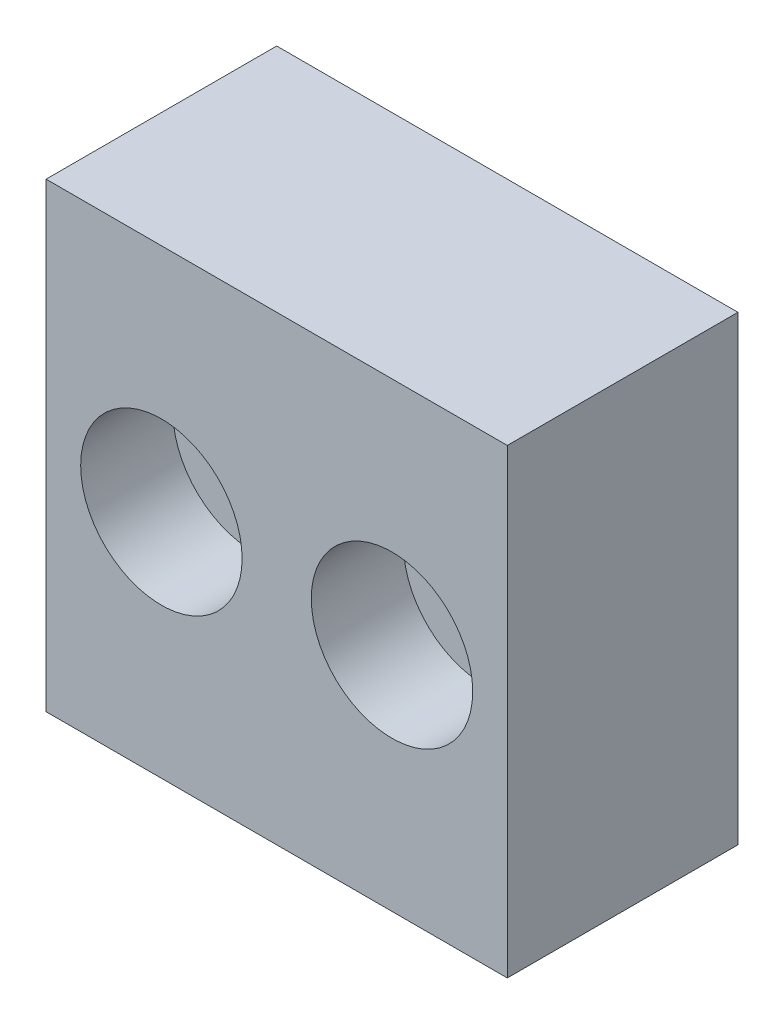
SolidWorks part; units mm, degrees
material "ASTM A36 Aço"
ref_plane "Plano frontal" through (0, 0, 0) normal (0, 0, 1) x (1, 0, 0)
ref_plane "Plano superior" through (0, 0, 0) normal (0, 1, 0) x (1, 0, 0)
ref_plane "Plano direito" through (0, 0, 0) normal (1, 0, 0) x (0, 0, -1)
sketch "Esboço1" plane through (0, 0, 0) normal (0, 0, 1) x (1, 0, 0)
  line L1 (-10, 10) -> (10, 10)
  line L2 (-10, 10) -> (-10, -10)
  line L3 (-10, -10) -> (10, -10)
  line L4 (10, 10) -> (10, -10)
  line L5 (-10, 10) -> (10, -10) construction
  line L6 (-10, -10) -> (10, 10) construction
  point P0 (0, 0)
  dimension "D1" = 20
extrude "Ressalto-extrusão1" add sketch "Esboço1" along normal blind 10
hole_wizard "Rebaixo para parafuso com cabeça panela de M41" positions "Esboço2" profile "Esboço3" counterbore size "M4" standard "ISO" end condition through all
sketch "Esboço2" plane through (0, 0, 10) normal (0, 0, 1) x (1, 0, 0)
  line L2 (-10, 10) -> (-10, -10) construction
  point P0 (5, 0)
  point P2 (-5, 0)
  point P14 (0, 5.1762)
  point P15 (0, 0)
  point P16 (-5.577, 0)
  point P19 (6.4632, 0)
  dimension "D1" = 5
  dimension "D2" = 10
sketch "Esboço3" plane through (5, 0, 10) normal (1, 0, 0) x (0, -1, 0)
  line L0 (0, 0) -> (0, 10)
  line L1 (0, 10) -> (2.15, 10)
  line L3 (2.15, 10) -> (2.15, 4)
  line L4 (2.15, 4) -> (3.5, 4)
  line L5 (3.5, 4) -> (3.5, 0)
  line L7 (3.5, 0) -> (0, 0)
  line L11 (0, -6.35) -> (0, 107.95) construction
  dimension "Thru Hole Dia." = 4.3
  dimension "Thru Hole Depth" = 10
  dimension "C'Bore Dia." = 7
  dimension "C'Bore Depth" = 4
